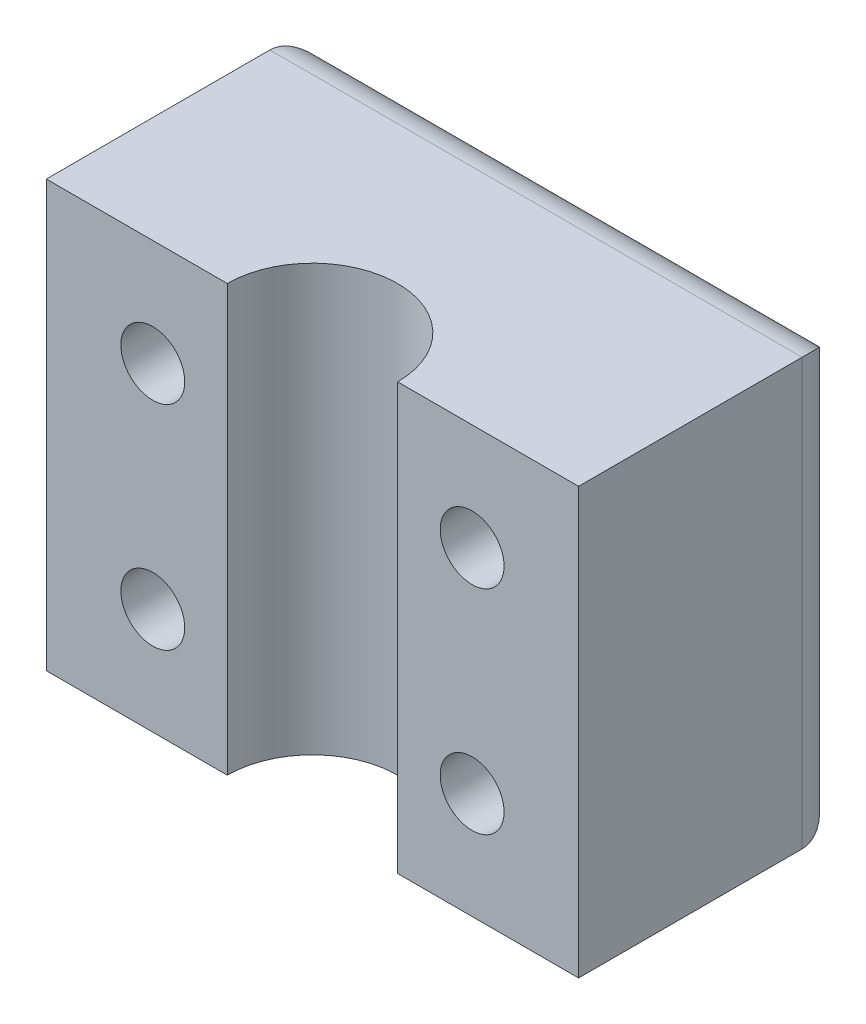
SolidWorks part; units mm, degrees
ref_plane "Front Plane" through (0, 0, 0) normal (0, 0, 1) x (1, 0, 0)
ref_plane "Top Plane" through (0, 0, 0) normal (0, 1, 0) x (1, 0, 0)
ref_plane "Right Plane" through (0, 0, 0) normal (1, 0, 0) x (0, 0, -1)
sketch "Sketch1" plane through (0, 0, 0) normal (0, 0, 1) x (1, 0, 0)
  line L1 (0, 0) -> (50, 0)
  line L2 (0, 0) -> (0, 40)
  line L3 (0, 40) -> (50, 40)
  line L4 (50, 0) -> (50, 40)
  dimension "D1" = 40
  dimension "D2" = 50
extrude "Boss-Extrude1" add sketch "Sketch1" along normal blind 25
sketch "Sketch2" plane through (0, 40, 0) normal (0, 1, 0) x (1, 0, 0)
  line L0 (50, -25) -> (0, -25) construction
  circle A0 centre (25, -25) radius 8
  dimension "D1" = 16
extrude "Cut-Extrude1" cut sketch "Sketch2" against normal blind 43
sketch "Sketch3" plane through (0, 0, 25) normal (0, 0, 1) x (1, 0, 0)
  line L0 (17, 40) -> (0, 40) construction
  line L1 (0, 0) -> (17, 0) construction
  line L2 (33, 0) -> (50, 0) construction
  line L3 (50, 40) -> (33, 40) construction
  line L4 (0, 40) -> (0, 0) construction
  line L5 (50, 0) -> (50, 40) construction
  circle A0 centre (10, 30) radius 3
  circle A1 centre (10, 10) radius 3
  circle A2 centre (40, 30) radius 3
  circle A3 centre (40, 10) radius 3
  dimension "D1" = 6
  dimension "D2" = 6
  dimension "D3" = 6
  dimension "D4" = 6
  dimension "D5" = 10
  dimension "D7" = 10
  dimension "D8" = 10
  dimension "D9" = 10
  dimension "D10" = 10
  dimension "D11" = 10
  dimension "D12" = 10
  dimension "D6" = 10
extrude "Cut-Extrude2" cut sketch "Sketch3" against normal blind 43
sketch "Sketch4" plane through (0, 0, 0) normal (0, 0, -1) x (-1, 0, 0)
  line L0 (0, 0) -> (-50, 0) construction
  line L1 (-7.1132, 5) -> (-4.2265, 10)
  line L2 (-4.2265, 10) -> (-7.1132, 15)
  line L3 (-7.1132, 15) -> (-12.8868, 15)
  line L4 (-12.8868, 15) -> (-15.7735, 10)
  line L5 (-15.7735, 10) -> (-12.8868, 5)
  line L6 (-12.8868, 5) -> (-7.1132, 5)
  line L7 (-37.1132, 5) -> (-34.2265, 10)
  line L8 (-34.2265, 10) -> (-37.1132, 15)
  line L9 (-37.1132, 15) -> (-42.8868, 15)
  line L10 (-42.8868, 15) -> (-45.7735, 10)
  line L11 (-45.7735, 10) -> (-42.8868, 5)
  line L12 (-42.8868, 5) -> (-37.1132, 5)
  line L13 (-7.1132, 25) -> (-4.2265, 30)
  line L14 (-4.2265, 30) -> (-7.1132, 35)
  line L15 (-7.1132, 35) -> (-12.8868, 35)
  line L16 (-12.8868, 35) -> (-15.7735, 30)
  line L17 (-15.7735, 30) -> (-12.8868, 25)
  line L18 (-12.8868, 25) -> (-7.1132, 25)
  line L19 (-42.8868, 35) -> (-45.7735, 30)
  line L20 (-45.7735, 30) -> (-42.8868, 25)
  line L21 (-42.8868, 25) -> (-37.1132, 25)
  line L22 (-37.1132, 25) -> (-34.2265, 30)
  line L23 (-34.2265, 30) -> (-37.1132, 35)
  line L24 (-37.1132, 35) -> (-42.8868, 35)
  line L25 (-50, 40) -> (0, 40) construction
  circle A0 centre (-10, 10) radius 5 construction
  circle A1 centre (-40, 10) radius 5 construction
  circle A2 centre (-10, 30) radius 5 construction
  circle A3 centre (-40, 30) radius 5 construction
  dimension "D1" = 10
  dimension "D2" = 10
  dimension "D3" = 10
  dimension "D4" = 10
  dimension "D5" = 0
  dimension "D6" = 0
  dimension "D7" = 0
  dimension "D8" = 0
extrude "Cut-Extrude3" cut sketch "Sketch4" against normal blind 5
fillet "Fillet1" radius 4 4 edges at (50, 20, 0) (25, 40, 0) (25, 0, 0) (0, 20, 0)
